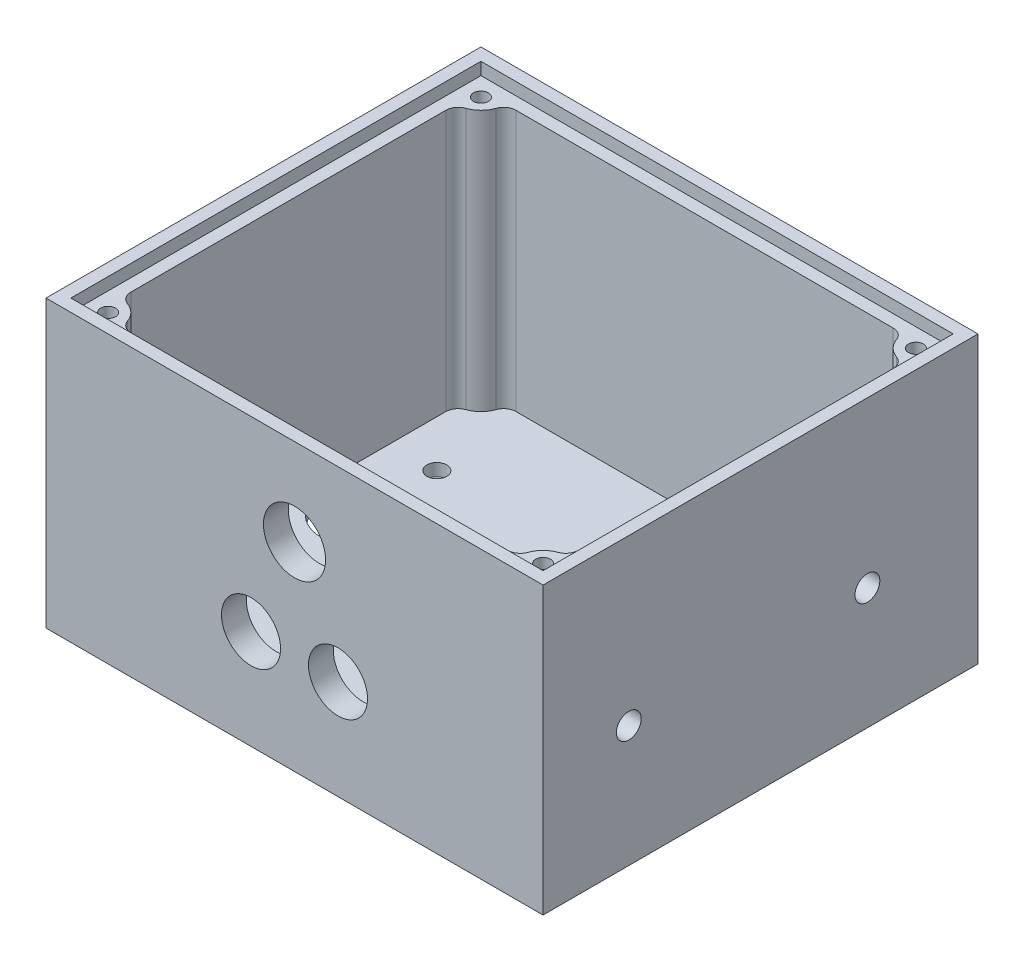
SolidWorks part; units mm, degrees
ref_plane "Front Plane" through (0, 0, 0) normal (0, 0, 1) x (1, 0, 0)
ref_plane "Top Plane" through (0, 0, 0) normal (0, 1, 0) x (1, 0, 0)
ref_plane "Right Plane" through (0, 0, 0) normal (1, 0, 0) x (0, 0, -1)
sketch "Sketch1" plane through (0, 0, 0) normal (0, 1, 0) x (1, 0, 0)
  line L1 (0, 0) -> (101.6, 0)
  line L2 (0, 0) -> (0, 88.9)
  line L3 (0, 88.9) -> (101.6, 88.9)
  line L4 (101.6, 0) -> (101.6, 88.9)
  dimension "D1" = 101.6
  dimension "D2" = 88.9
extrude "Boss-Extrude1" add sketch "Sketch1" along normal blind 58.42
sketch "Sketch2" plane through (0, 58.42, 0) normal (0, 1, 0) x (1, 0, 0)
  line L0 (101.6, 0) -> (101.6, 88.9) construction
  line L1 (5.08, 83.82) -> (96.52, 83.82)
  line L2 (5.08, 83.82) -> (5.08, 5.08)
  line L3 (5.08, 5.08) -> (96.52, 5.08)
  line L4 (96.52, 83.82) -> (96.52, 5.08)
  line L5 (101.6, 88.9) -> (0, 88.9) construction
  line L6 (0, 88.9) -> (0, 0) construction
  line L7 (0, 0) -> (101.6, 0) construction
  dimension "D1" = 5.08
  dimension "D2" = 5.08
  dimension "D3" = 5.08
  dimension "D4" = 5.08
extrude "Cut-Extrude1" cut sketch "Sketch2" against normal offset from surface (55.88 mm away) 2.54 up to face at (50.8, 0, -44.45)
sketch "Sketch3" plane through (0, 2.54, 0) normal (0, 1, 0) x (1, 0, 0)
  line L0 (14.605, 69.85) -> (14.605, 19.05) construction
  line L1 (5.08, 69.85) -> (24.13, 69.85) construction
  line L2 (5.08, 69.85) -> (5.08, 19.05) construction
  line L3 (5.08, 19.05) -> (24.13, 19.05) construction
  line L4 (24.13, 69.85) -> (24.13, 19.05) construction
  line L6 (5.08, 83.82) -> (5.08, 5.08) construction
  circle A0 centre (14.605, 49.53) radius 7.874
  circle A1 centre (14.605, 65.278) radius 2.032
  circle A2 centre (14.605, 23.368) radius 2.032
  point P17 (5.08, 44.45)
  point P18 (5.08, 44.45)
  dimension "D1" = 15.748
  dimension "D5" = 4.064
  dimension "D2" = 50.8
  dimension "D3" = 19.05
  dimension "D4" = 20.32
  dimension "D6" = 4.572
  dimension "D7" = 41.91
  dimension "D8" = 0
  dimension "D9" = 0
extrude "Cut-Extrude2" cut sketch "Sketch3" against normal through all
sketch "Sketch5" plane through (0, 2.54, 0) normal (0, 1, 0) x (1, 0, 0)
  line L0 (5.08, 83.82) -> (5.08, 5.08) construction
  line L1 (96.52, 83.82) -> (5.08, 83.82) construction
  arc A0 (49.2794, 55.7784) -> (52.3206, 55.7784) centre (50.8, 44.45) ccw
  arc A1 (49.2794, 55.7784) -> (52.3206, 55.7784) centre (50.8, 55.88) cw
  point P4 (5.08, 44.45)
  point P7 (50.8, 83.82)
  dimension "D1" = 22.86
  dimension "D4" = 1.524
  dimension "D2" = 0
  dimension "D3" = 0
extrude "Cut-Extrude3" cut sketch "Sketch5" against normal through all
sketch "Sketch6" plane through (96.52, 0, 0) normal (-1, 0, 0) x (0, 0, 1)
  line L0 (-12.7, 24.765) -> (-71.12, 24.765) construction
  line L1 (-71.12, 2.54) -> (-12.7, 2.54) construction
  line L2 (-71.12, 2.54) -> (-71.12, 46.99) construction
  line L3 (-71.12, 46.99) -> (-12.7, 46.99) construction
  line L4 (-12.7, 2.54) -> (-12.7, 46.99) construction
  line L5 (-5.08, 2.54) -> (-83.82, 2.54) construction
  circle A0 centre (-17.526, 24.765) radius 2.54
  circle A1 centre (-66.294, 24.765) radius 2.54
  point P8 (-41.91, 2.54)
  point P13 (-44.45, 2.54)
  dimension "D3" = 5.08
  dimension "D1" = 44.45
  dimension "D2" = 58.42
  dimension "D4" = 4.826
  dimension "D5" = 4.826
  dimension "D6" = 0
  dimension "D7" = 2.54
extrude "Cut-Extrude4" cut sketch "Sketch6" against normal through all
sketch "Sketch8" plane through (0, 0, -5.08) normal (0, 0, -1) x (-1, 0, 0)
  line L0 (-41.91, 20.32) -> (-59.69, 20.32) construction
  line L1 (-5.08, 58.42) -> (-96.52, 58.42) construction
  circle A0 centre (-41.91, 20.32) radius 6.0325
  circle A1 centre (-59.69, 20.32) radius 6.0325
  point P4 (-50.8, 20.32)
  point P7 (-50.8, 58.42)
  dimension "D1" = 12.065
  dimension "D2" = 17.78
  dimension "D3" = 38.1
extrude "Cut-Extrude5" cut sketch "Sketch8" against normal through all
sketch "Sketch9" plane through (0, 58.42, 0) normal (0, 1, 0) x (1, 0, 0)
  line L0 (96.52, 5.08) -> (96.52, 83.82) construction
  line L1 (2.54, 86.36) -> (99.06, 86.36)
  line L2 (2.54, 86.36) -> (2.54, 2.54)
  line L3 (2.54, 2.54) -> (99.06, 2.54)
  line L4 (99.06, 86.36) -> (99.06, 2.54)
  line L5 (96.52, 83.82) -> (5.08, 83.82) construction
  line L6 (5.08, 83.82) -> (5.08, 5.08) construction
  line L7 (5.08, 5.08) -> (96.52, 5.08) construction
  dimension "D1" = 2.54
  dimension "D2" = 2.54
  dimension "D3" = 2.54
  dimension "D4" = 2.54
extrude "Cut-Extrude6" cut sketch "Sketch9" against normal blind 2.54
sketch "Sketch10" plane through (0, 0, -5.08) normal (0, 0, -1) x (-1, 0, 0)
  line L0 (-96.52, 55.88) -> (-5.08, 55.88) construction
  circle A0 centre (-50.8, 40.64) radius 6.35
  point P4 (-50.8, 55.88)
  dimension "D1" = 12.7
  dimension "D2" = 15.24
extrude "Cut-Extrude7" cut sketch "Sketch10" against normal through all
sketch "Sketch11" plane through (0, 2.54, 0) normal (0, 1, 0) x (1, 0, 0)
  line L0 (5.08, 83.82) -> (5.08, 5.08) construction
  line L1 (5.08, 5.08) -> (96.52, 5.08) construction
  line L2 (96.52, 5.08) -> (96.52, 83.82) construction
  line L3 (96.52, 83.82) -> (5.08, 83.82) construction
  line L4 (10.16, 83.82) -> (5.08, 83.82)
  line L5 (5.08, 83.82) -> (5.08, 78.74)
  line L6 (5.08, 10.16) -> (5.08, 5.08)
  line L7 (5.08, 5.08) -> (10.16, 5.08)
  line L8 (96.52, 10.16) -> (96.52, 5.08)
  line L9 (96.52, 5.08) -> (91.44, 5.08)
  line L10 (96.52, 78.74) -> (96.52, 83.82)
  line L11 (96.52, 83.82) -> (91.44, 83.82)
  arc A0 (5.08, 10.16) -> (10.16, 5.08) centre (5.08, 5.08) cw
  arc A1 (96.52, 10.16) -> (91.44, 5.08) centre (96.52, 5.08) ccw
  arc A2 (96.52, 78.74) -> (91.44, 83.82) centre (96.52, 83.82) cw
  arc A3 (10.16, 83.82) -> (5.08, 78.74) centre (5.08, 83.82) cw
  dimension "D1" = 5.08
extrude "Boss-Extrude2" add sketch "Sketch11" along normal up to surface (53.34 mm away) up to face at (50.8, 55.88, -44.45)
fillet "Fillet1" radius 2.54 8 edges at (91.44, 29.21, -83.82) (96.52, 29.21, -78.74) (96.52, 29.21, -10.16) (91.44, 29.21, -5.08) (10.16, 29.21, -5.08) (5.08, 29.21, -10.16) (5.08, 29.21, -78.74) (10.16, 29.21, -83.82)
sketch "Sketch13" plane through (0, 55.88, 0) normal (0, 1, 0) x (1, 0, 0)
  line L0 (99.06, 86.36) -> (2.54, 86.36) construction
  line L1 (2.54, 86.36) -> (2.54, 2.54) construction
  line L2 (99.06, 2.54) -> (99.06, 86.36) construction
  line L3 (2.54, 2.54) -> (99.06, 2.54) construction
  circle A0 centre (6.35, 82.55) radius 1.524
  circle A1 centre (95.25, 82.55) radius 1.524
  circle A2 centre (95.25, 6.35) radius 1.524
  circle A3 centre (6.35, 6.35) radius 1.524
  dimension "D1" = 3.048
  dimension "D2" = 3.81
  dimension "D3" = 3.81
  dimension "D4" = 3.81
  dimension "D5" = 3.81
extrude "Cut-Extrude8" cut sketch "Sketch13" against normal blind 12.7
